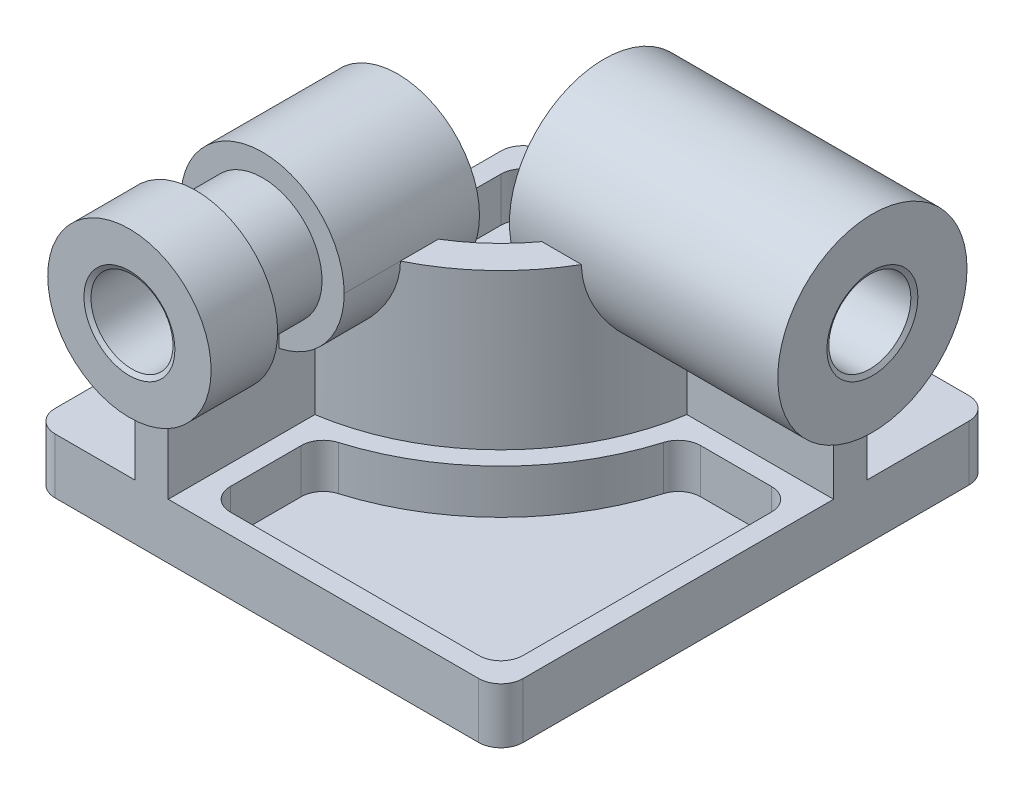
SolidWorks part; units mm, degrees
material "Alloy Steel"
ref_plane "Front Plane" through (0, 0, 0) normal (0, 0, 1) x (1, 0, 0)
ref_plane "Top Plane" through (0, 0, 0) normal (0, 1, 0) x (1, 0, 0)
ref_plane "Right Plane" through (0, 0, 0) normal (1, 0, 0) x (0, 0, -1)
sketch "Sketch1" plane through (0, 0, 0) normal (0, 1, 0) x (1, 0, 0)
  line L0 (0, 0) -> (0, -165) construction
  line L1 (-36, 56) -> (155, 56)
  line L2 (-46, 46) -> (-46, -155)
  line L3 (-36, -165) -> (155, -165)
  line L4 (165, 46) -> (165, -155)
  line L6 (21.1729, -100.3509) -> (22.0551, -100.3509) construction
  line L8 (0, 0) -> (165, 0) construction
  arc A0 (-36, 56) -> (-46, 46) centre (-36, 46) ccw
  arc A1 (-46, -155) -> (-36, -165) centre (-36, -155) ccw
  arc A2 (155, -165) -> (165, -155) centre (155, -155) ccw
  arc A3 (155, 56) -> (165, 46) centre (155, 46) cw
  dimension "D5" = 10
  dimension "D1" = 165
  dimension "D2" = 165
  dimension "D3" = 221
  dimension "D4" = 211
extrude "Boss-Extrude1" add sketch "Sketch1" along normal blind 25
sketch "Sketch2" plane through (0, 25, 0) normal (0, 1, 0) x (1, 0, 0)
  line L0 (0, -85) -> (0, -165)
  line L1 (-36, -165) -> (155, -165) construction
  line L2 (85, 0) -> (165, 0)
  line L3 (165, -155) -> (165, 46) construction
  line L4 (15, -98.8686) -> (15, -165)
  line L5 (98.8686, -15) -> (165, -15)
  line L6 (165, 0) -> (165, -15)
  line L7 (0, -165) -> (15, -165)
  arc A0 (0, -85) -> (85, 0) centre (0, 0) ccw
  arc A1 (15, -98.8686) -> (98.8686, -15) centre (0, 0) ccw
  dimension "D1" = 80
  dimension "D2" = 15
extrude "Boss-Extrude2" add sketch "Sketch2" along normal blind 95 from surface at -25 starting at face at (59.5, 0, 54.5)
sketch "Sketch3" plane through (0, 25, 0) normal (0, 1, 0) x (1, 0, 0)
  line L0 (15, -165) -> (155, -165) construction
  line L1 (120, -105) -> (165, -105)
  line L2 (105, -120) -> (105, -165)
  line L3 (105, -165) -> (155, -165)
  line L4 (165, -105) -> (165, -155)
  line L5 (165, -155) -> (165, -15) construction
  arc A0 (155, -165) -> (165, -155) centre (155, -155) ccw construction
  arc A1 (155, -165) -> (165, -155) centre (155, -155) ccw
  arc A2 (120, -105) -> (105, -120) centre (120, -120) ccw
  dimension "D3" = 15
  dimension "D1" = 60
  dimension "D2" = 60
extrude "Boss-Extrude3" [suppressed] add sketch "Sketch3" along normal blind 10
hole_wizard "CBORE for M8 Hex Head Bolt1" [suppressed] positions "Sketch5" profile "Sketch4" counterbore size "M8" standard "ANSI Metric"
sketch "Sketch5" [suppressed] plane through (0, 35, 0) normal (0, 1, 0) x (1, 0, 0)
  line L0 (105, -165) -> (155, -165) construction
  line L2 (165, -155) -> (165, -105) construction
  point P0 (135, -135)
  dimension "D1" = 30
  dimension "D2" = 30
sketch "Sketch4" plane through (135, 35, 135) normal (1, 0, 0) x (0, 0, 1)
  line L0 (0, 0) -> (0, 35)
  line L1 (0, 35) -> (7.5, 35)
  line L3 (7.5, 35) -> (7.5, 10)
  line L4 (7.5, 10) -> (15, 10)
  line L5 (15, 10) -> (15, 0)
  line L7 (15, 0) -> (0, 0)
  line L11 (0, -6.35) -> (0, 107.95) construction
  dimension "Thru Hole Dia." = 15
  dimension "Thru Hole Depth" = 35
  dimension "C'Bore Dia." = 30
  dimension "C'Bore Depth" = 10
sketch "Sketch6" plane through (0, 25, 0) normal (0, 1, 0) x (1, 0, 0)
  line L10 (156, -24) -> (106.325, -24)
  line L11 (156, -24) -> (106.325, -24)
  line L12 (24, -156) -> (155, -156)
  line L13 (24, -106.325) -> (24, -156)
  line L14 (24, -106.325) -> (24, -156)
  line L15 (156, -155) -> (156, -24)
  line L18 (20, -156) -> (86, -156)
  line L21 (156, -145) -> (156, -38)
  arc A2 (114.0395, -24) -> (104.4563, -31.1429) centre (114.0395, -34) ccw
  arc A3 (156, -38) -> (149.7139, -28.7152) centre (146, -38) ccw
  arc A4 (155, -156) -> (156, -155) centre (155, -155) ccw
  arc A5 (24, -106.325) -> (106.325, -24) centre (0, 0) ccw
  arc A6 (155, -156) -> (156, -155) centre (155, -155) ccw
  arc A7 (24, -106.325) -> (106.325, -24) centre (0, 0) ccw
  arc A8 (146.2743, -154.9962) -> (156, -145) centre (146, -145) ccw
  arc A9 (86, -156) -> (95.9962, -146.2743) centre (86, -146) ccw
  arc A10 (20, -156) -> (10.7152, -149.7139) centre (20, -146) cw
  arc A11 (31.1429, -104.4563) -> (24, -114.0395) centre (34, -114.0395) ccw
  dimension "D2" = 10
  dimension "D1" = 9
extrude "Cut-Extrude1" [suppressed] cut sketch "Sketch6" against normal offset from surface (20 mm away) 5
sketch "Sketch7" plane through (0, 0, 165) normal (0, 0, 1) x (1, 0, 0)
  line L0 (0, 95) -> (15, 95) construction
  circle A0 centre (7.5, 95) radius 36.8333
  dimension "D1" = 73.6667
extrude "Boss-Extrude4" add sketch "Sketch7" against normal blind 121 from offset 10
sketch "Sketch8" plane through (165, 0, 0) normal (1, 0, 0) x (0, 0, -1)
  line L0 (-15, 95) -> (0, 95) construction
  circle A0 centre (-7.5, 95) radius 42.6667
  dimension "D1" = 85.3333
extrude "Boss-Extrude5" add sketch "Sketch8" against normal blind 121 from offset 10
sketch "Sketch9" plane through (0, 0, 175) normal (0, 0, 1) x (1, 0, 0)
  circle A0 centre (7.5, 95) radius 18.5
  dimension "D1" = 37
extrude "Cut-Extrude2" cut sketch "Sketch9" against normal up to next
sketch "Sketch10" plane through (175, 0, 0) normal (1, 0, 0) x (0, 0, -1)
  circle A0 centre (-7.5, 95) radius 18.5
  dimension "D1" = 37
extrude "Cut-Extrude3" cut sketch "Sketch10" against normal up to next
chamfer "Chamfer1" distance 2 angle 30 4 edges at (54, 95, -11) (26, 95, 54) (175, 95, -11) (26, 95, 175)
sketch "Sketch11" plane through (0, 0, 175) normal (0, 0, 1) x (1, 0, 0)
  line L0 (0, 58.9383) -> (0, 69.2361)
  line L2 (15, 69.2361) -> (15, 58.9383)
  arc A0 (15, 69.2361) -> (0, 69.2361) centre (7.5, 95) ccw
  circle A1 centre (7.5, 95) radius 36.8333 construction
  arc A2 (15, 58.9383) -> (0, 58.9383) centre (7.5, 95) ccw
  dimension "D1" = 10
extrude "Cut-Extrude4" cut sketch "Sketch11" against normal blind 30 from offset 30 offset against normal yes
sketch "Sketch12" plane through (0, 25, 0) normal (0, 1, 0) x (1, 0, 0)
  line L8 (24, -106.325) -> (24, -156)
  line L9 (24, -156) -> (155, -156)
  line L10 (156, -155) -> (156, -24)
  line L11 (24, -114.0395) -> (24, -146)
  line L12 (156, -24) -> (106.325, -24)
  line L13 (34, -156) -> (146, -156)
  line L14 (156, -146) -> (156, -34)
  line L15 (146, -24) -> (114.0395, -24)
  arc A2 (156, -146) -> (146, -156) centre (146, -146) cw
  arc A3 (34, -156) -> (24, -146) centre (34, -146) cw
  arc A4 (24, -106.325) -> (106.325, -24) centre (0, 0) ccw
  arc A5 (155, -156) -> (156, -155) centre (155, -155) ccw
  arc A6 (31.1429, -104.4563) -> (104.4563, -31.1429) centre (0, 0) ccw
  arc A7 (155, -156) -> (156, -155) centre (155, -155) ccw construction
  arc A8 (31.1429, -104.4563) -> (24, -114.0395) centre (34, -114.0395) ccw
  arc A9 (114.0395, -24) -> (104.4563, -31.1429) centre (114.0395, -34) ccw
  arc A10 (156, -34) -> (146, -24) centre (146, -34) ccw
  dimension "D2" = 10
  dimension "D3" = 10
  dimension "D1" = 9
extrude "Cut-Extrude5" cut sketch "Sketch12" against normal offset from surface (20 mm away) 5 up to face at (59.5, 0, 54.5)
sketch "Sketch13" plane through (0, 25, 0) normal (0, 1, 0) x (1, 0, 0)
  line L7 (76, 0) -> (76, 37)
  line L8 (0, -76) -> (-27, -76)
  line L13 (156, 9) -> (156, 46)
  line L14 (155, 47) -> (-36, 47)
  line L15 (-37, 46) -> (-37, -155)
  line L16 (-36, -156) -> (-9, -156)
  line L18 (75.4652, 9) -> (156, 9)
  line L19 (-9, -156) -> (-9, -75.4652)
  line L20 (66, 47) -> (-27, 47)
  line L21 (-37, 37) -> (-37, -66)
  arc A4 (-27, -76) -> (-37, -66) centre (-27, -66) cw
  arc A5 (76, 37) -> (66, 47) centre (66, 37) ccw
  arc A6 (-27, 47) -> (-37, 37) centre (-27, 37) ccw
  arc A8 (-9, -75.4652) -> (75.4652, 9) centre (0, 0) ccw
  arc A9 (156, 46) -> (155, 47) centre (155, 46) ccw
  arc A10 (-36, 47) -> (-37, 46) centre (-36, 46) ccw
  arc A11 (-37, -155) -> (-36, -156) centre (-36, -155) ccw
  arc A12 (0, -76) -> (76, 0) centre (0, 0) ccw
  arc A14 (-36, 47) -> (-37, 46) centre (-36, 46) ccw construction
  dimension "D2" = 10
  dimension "D3" = 10
  dimension "D1" = 9
extrude "Cut-Extrude7" cut sketch "Sketch13" against normal up to surface (20 mm away) up to face at (94.4211, 5, 94.4211)
equation "\"A\"= 221"
equation "\"D1@Sketch1\"=\"C\""
equation "\"D2@Sketch1\"=\"C\""
equation "\"B\"= 211"
equation "\"D3@Sketch1\"=\"A\""
equation "\"C\"= 165"
equation "\"D4@Sketch1\"=\"B\""
equation "\"D1@Sketch7\"=\"X\""
equation "\"D\"= 121"
equation "\"D1@Boss-Extrude4\"=\"D\""
equation "\"D1@Sketch8\"=\"Y\""
equation "\"D1@Boss-Extrude5\"=\"D\""
equation "\"E\"= 37"
equation "\"D1@Sketch9\"=\"E\""
equation "\"D1@Sketch10\"=\"E\""
equation "\"X\"= \"A\" / 3"
equation "\"Y\"= \"B\" / 3 + 15"
